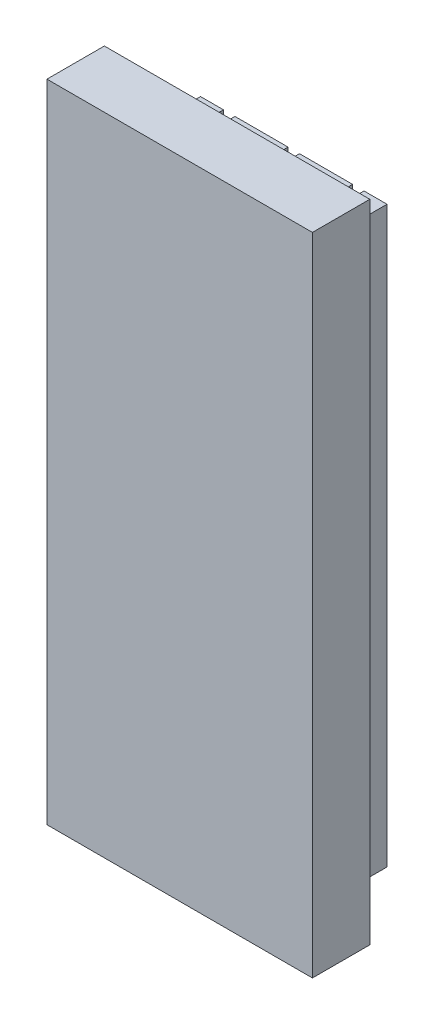
SolidWorks part; units mm, degrees
ref_plane "Front Plane" through (0, 0, 0) normal (0, 0, 1) x (1, 0, 0)
ref_plane "Top Plane" through (0, 0, 0) normal (0, 1, 0) x (1, 0, 0)
ref_plane "Right Plane" through (0, 0, 0) normal (1, 0, 0) x (0, 0, -1)
sketch "Sketch1" plane through (0, 0, 0) normal (0, 1, 0) x (1, 0, 0)
  line L0 (-130, 90) -> (-130, 0) construction
  line L1 (-260, 90) -> (0, 90)
  line L2 (-260, 90) -> (-260, 0)
  line L3 (-260, 0) -> (0, 0)
  line L4 (0, 90) -> (0, 0)
  line L5 (-48, 90) -> (-48, 81)
  line L6 (-48, 81) -> (-56, 81)
  line L7 (-56, 81) -> (-56, 72)
  line L8 (-56, 72) -> (-24, 72)
  line L9 (-24, 72) -> (-24, 81)
  line L10 (-24, 81) -> (-32, 81)
  line L11 (-32, 81) -> (-32, 90)
  line L12 (-40, 72) -> (-40, 90) construction
  line L13 (-85, 90) -> (-85, 0) construction
  line L14 (-48, 90) -> (-32, 90)
  line L15 (-122, 90) -> (-122, 81)
  line L16 (-122, 81) -> (-114, 81)
  line L17 (-114, 81) -> (-114, 72)
  line L18 (-114, 72) -> (-146, 72)
  line L19 (-146, 72) -> (-146, 81)
  line L20 (-146, 81) -> (-138, 81)
  line L21 (-138, 81) -> (-138, 90)
  line L22 (-122, 90) -> (-138, 90)
  line L23 (-212, 90) -> (-212, 81)
  line L24 (-212, 81) -> (-204, 81)
  line L25 (-204, 81) -> (-204, 72)
  line L26 (-204, 72) -> (-236, 72)
  line L27 (-236, 72) -> (-236, 81)
  line L28 (-236, 81) -> (-228, 81)
  line L29 (-228, 81) -> (-228, 90)
  line L30 (-212, 90) -> (-228, 90)
  point P27 (-130, 72)
  dimension "D1" = 90
  dimension "D2" = 260
  dimension "D3" = 16
  dimension "D4" = 32
  dimension "D5" = 9
  dimension "D6" = 18
  dimension "D7" = 90
extrude "Boss-Extrude1" add sketch "Sketch1" along normal blind 800 contours L28 L29 L1 L2 L3 L4 L11 L10 L9 L8 L7 L6 L5 L15 L16 L17 L18 L19 L20 L21 L23 L24 L25 L26 L27
sketch "Sketch2" plane through (0, 0, 0) normal (0, -1, 0) x (1, 0, 0)
  line L1 (-338, -34) -> (32, -34)
  line L2 (-338, -34) -> (-338, 46)
  line L3 (-338, 46) -> (32, 46)
  line L4 (32, -34) -> (32, 46)
  line L6 (-260, -90) -> (-228, -90) construction
  line L7 (-260, -90) -> (-260, 0) construction
  dimension "D1" = 56
  dimension "D2" = 78
  dimension "D3" = 370
  dimension "D4" = 80
extrude "Boss-Extrude2" add sketch "Sketch2" against normal blind 850 and the other way blind 50
